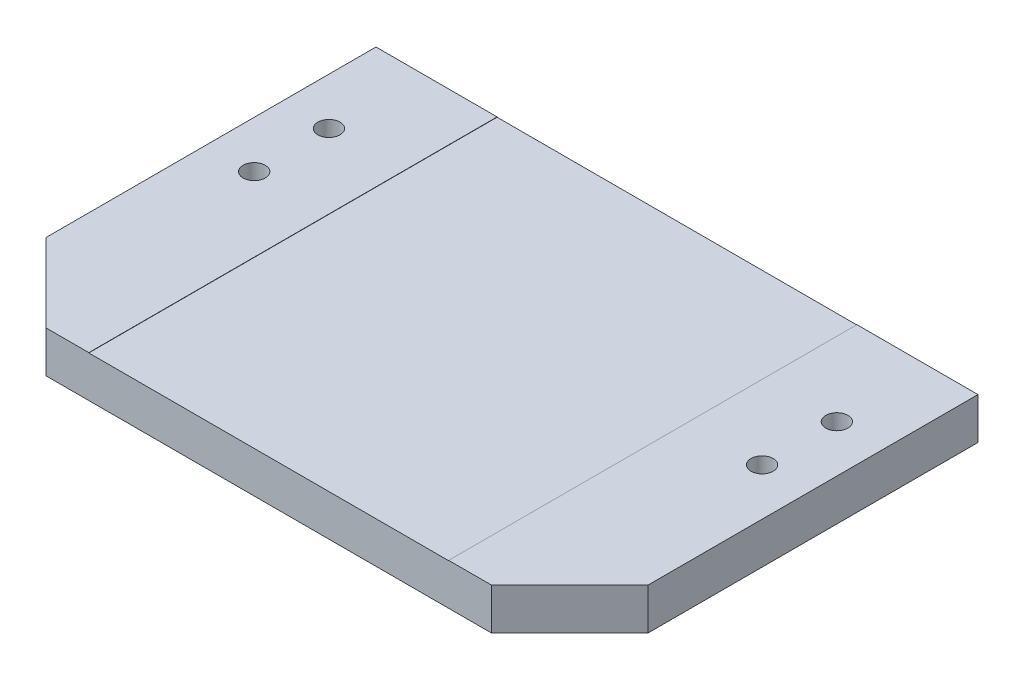
SolidWorks part; units mm, degrees
ref_plane "Plan de face" through (0, 0, 0) normal (0, 0, 1) x (1, 0, 0)
ref_plane "Plan de dessus" through (0, 0, 0) normal (0, 1, 0) x (1, 0, 0)
ref_plane "Plan de droite" through (0, 0, 0) normal (1, 0, 0) x (0, 0, -1)
sketch "Esquisse1" plane through (0, 0, 0) normal (0, 1, 0) x (1, 0, 0)
  line L0 (-10.875, 7.375) -> (10.875, 7.375)
  line L1 (10.875, 7.375) -> (10.875, -4.5466)
  line L2 (10.875, -4.5466) -> (8.0466, -7.375)
  line L3 (8.0466, -7.375) -> (-8.0466, -7.375)
  line L4 (-8.0466, -7.375) -> (-10.875, -4.5466)
  line L5 (-10.875, -4.5466) -> (-10.875, 7.375)
  line L6 (0, 7.375) -> (0, -7.375) construction
  circle A0 centre (-9.175, 1.275) radius 0.4
  circle A1 centre (-9.175, 3.975) radius 0.4
  circle A2 centre (9.175, 1.275) radius 0.4
  circle A3 centre (9.175, 3.975) radius 0.4
  point P8 (0, 0)
  point P9 (0, -7.375)
  point P19 (-9.175, 4.375)
  point P20 (-9.175, 0.875)
  point P21 (-9.575, 3.975)
  point P22 (9.575, 3.975)
  dimension "D7" = 0.8
  dimension "D8" = 0.8
  dimension "D9" = 0.8
  dimension "D10" = 0.8
  dimension "D1" = 14.75
  dimension "D2" = 21.75
  dimension "D3" = 4
  dimension "D4" = 4
  dimension "D5" = 135
  dimension "D6" = 135
  dimension "D11" = 3.5
  dimension "D12" = 3
  dimension "D13" = 1.3
  dimension "D14" = 1.3
extrude "Boss.-Extru.1" add sketch "Esquisse1" along normal blind 1.5
sketch "Esquisse2" plane through (0, 1.5, 0) normal (0, 1, 0) x (1, 0, 0)
  line L0 (10.875, 7.375) -> (-10.875, 7.375) construction
  line L1 (-6.5, 7.375) -> (6.5, 7.375)
  line L2 (-6.5, 7.375) -> (-6.5, -7.375)
  line L3 (-6.5, -7.375) -> (6.5, -7.375)
  line L4 (6.5, 7.375) -> (6.5, -7.375)
  line L5 (-8.0466, -7.375) -> (8.0466, -7.375) construction
  point P8 (0, 7.375)
  dimension "D1" = 13
extrude "Enlèv. mat.-Extru.1" cut sketch "Esquisse2" against normal blind 0.01
